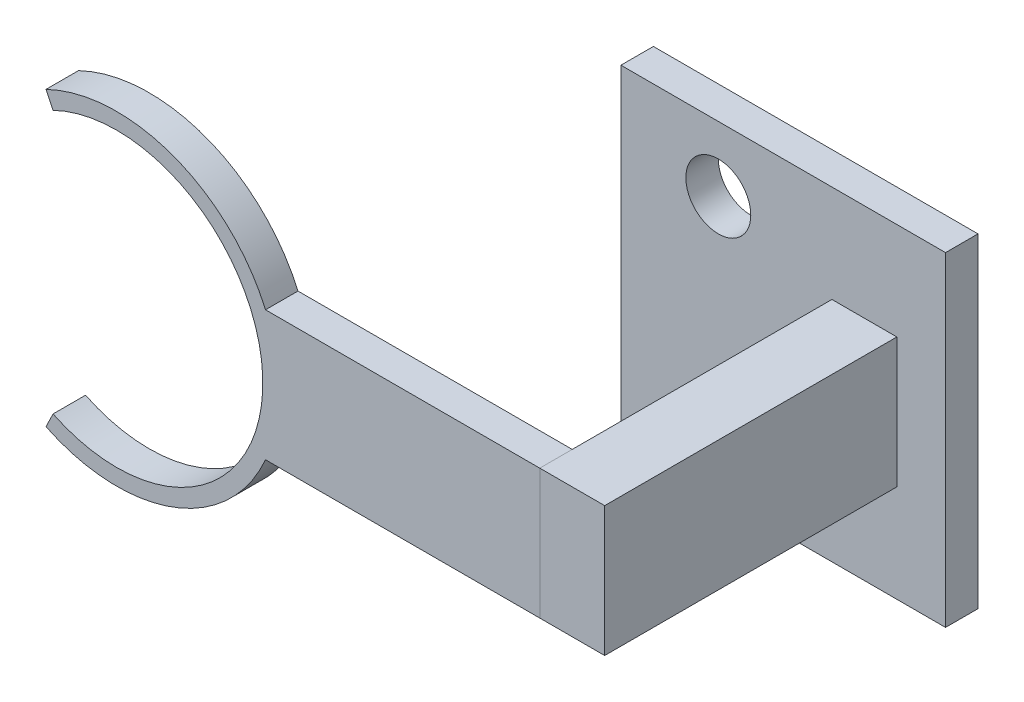
SolidWorks part; units mm, degrees
ref_plane "Front Plane" through (0, 0, 0) normal (0, 0, 1) x (1, 0, 0)
ref_plane "Top Plane" through (0, 0, 0) normal (0, 1, 0) x (1, 0, 0)
ref_plane "Right Plane" through (0, 0, 0) normal (1, 0, 0) x (0, 0, -1)
sketch "Sketch1" plane through (0, 0, 0) normal (0, 0, 1) x (1, 0, 0)
  line L1 (10, 10) -> (-10, 10)
  line L2 (10, 10) -> (10, -10)
  line L3 (10, -10) -> (-10, -10)
  line L4 (-10, 10) -> (-10, -10)
  circle A0 centre (-4, 6) radius 2
  circle A1 centre (-4, -6) radius 2
  point P0 (0, 0)
extrude "Boss-Extrude1" add sketch "Sketch1" along normal blind 2
sketch "Sketch2" plane through (0, 0, 2) normal (0, 0, 1) x (1, 0, 0)
  line L0 (0, 0) -> (5, 0)
  line L2 (7, 4) -> (3, 4)
  line L3 (7, 4) -> (7, -4)
  line L4 (7, -4) -> (3, -4)
  line L5 (3, 4) -> (3, -4)
  line L6 (7, 4) -> (3, -4) construction
  line L7 (7, -4) -> (3, 4) construction
extrude "Boss-Extrude2" add sketch "Sketch2" along normal blind 18
sketch "Sketch3" plane through (0, 0, 20) normal (0, 0, 1) x (1, 0, 0)
  line L0 (3, 4) -> (3, -4) construction
  line L1 (3, 0) -> (-10, 0)
  line L2 (-10, 10) -> (-10, -10) construction
  line L3 (-10, 0) -> (-6, 0)
  line L5 (-15, 4) -> (3, 4)
  line L7 (-15, -4) -> (3, -4)
  line L8 (3, 4) -> (3, -4)
  line L9 (-15, 4) -> (3, -4) construction
  line L10 (-15, -4) -> (3, 4) construction
  line L15 (-26.9853, 8.1) -> (-27.4212, 9)
  line L16 (-26.9853, -8.1) -> (-27.4212, -9)
  arc A0 (-26.9853, -8.1) -> (-26.9853, 8.1) centre (-23.0623, 0) ccw
  arc A1 (-27.4212, -9) -> (-27.4212, 9) centre (-23.0623, 0) ccw
extrude "Boss-Extrude3" add sketch "Sketch3" against normal blind 2 separate body
